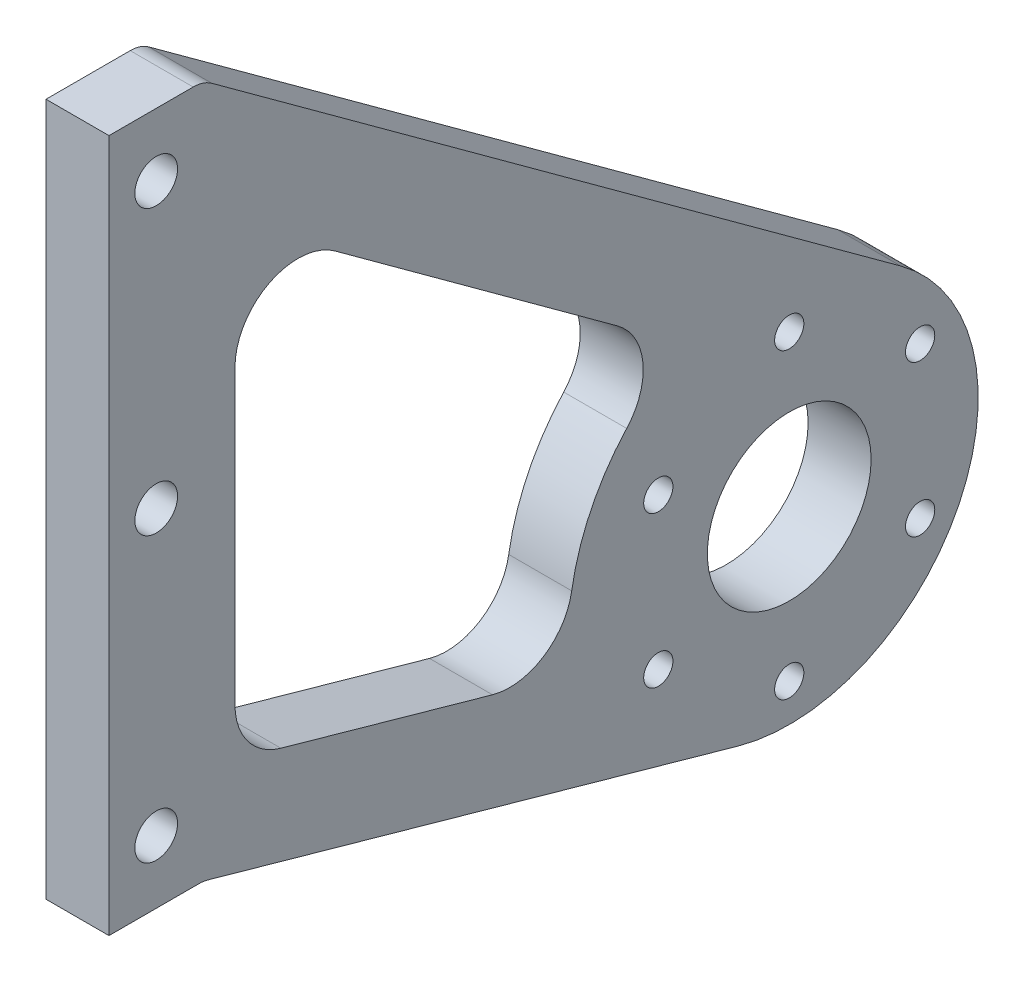
SolidWorks part; units mm, degrees
material "6061-T6 (SS)"
ref_plane "Front Plane" through (0, 0, 0) normal (0, 0, 1) x (1, 0, 0)
ref_plane "Top Plane" through (0, 0, 0) normal (0, 1, 0) x (1, 0, 0)
ref_plane "Right Plane" through (0, 0, 0) normal (1, 0, 0) x (0, 0, -1)
sketch "Sketch1" plane through (0, 0, 0) normal (1, 0, 0) x (0, 0, -1)
  line L0 (0, -34.925) -> (0, 34.925)
  line L1 (0, 34.925) -> (9.525, 34.925)
  line L2 (9.525, 34.925) -> (79.8091, -16.3614)
  line L4 (0, -34.925) -> (9.525, -34.925)
  line L5 (9.525, -34.925) -> (63.4208, -50.0881)
  arc A0 (79.8091, -16.3614) -> (63.4208, -50.0881) centre (68.58, -31.75) cw
  point P1 (0, 0)
  dimension "D5" = 19.05
  dimension "D1" = 69.85
  dimension "D2" = 9.525
  dimension "D3" = 68.58
  dimension "D4" = 31.75
extrude "Boss-Extrude1" add sketch "Sketch1" along normal mid plane 6.35
sketch "Sketch2" plane through (3.175, 0, 0) normal (1, 0, 0) x (0, 0, -1)
  circle A0 centre (68.58, -31.75) radius 8.255
  dimension "D1" = 16.51
extrude "Cut-Extrude1" cut sketch "Sketch2" against normal through all
hole_wizard "#8 Clearance Hole1" positions "Sketch4" profile "Sketch5" hole size "#8" standard "Ansi Inch" end condition through all
sketch "Sketch4" plane through (3.175, 0, 0) normal (1, 0, 0) x (0, 0, -1)
  line L0 (4.7625, 34.925) -> (4.7625, -34.925) construction
  line L2 (0, 34.925) -> (9.525, 34.925) construction
  line L4 (0, -34.925) -> (9.525, -34.925) construction
  point P0 (4.7625, 0)
  point P17 (4.7625, 28.575)
  point P19 (4.7625, -28.575)
  dimension "D1" = 28.575
  dimension "D2" = 28.575
sketch "Sketch5" plane through (3.175, 0, -4.7625) normal (0, 1, 0) x (0, 0, -1)
  line L0 (0, 0) -> (0, 6.35)
  line L1 (0, 6.35) -> (2.1526, 6.35)
  line L2 (2.1526, 6.35) -> (2.1526, 0)
  line L5 (2.1526, 0) -> (0, 0)
  line L11 (0, -6.35) -> (0, 107.95) construction
  dimension "Thru Hole Dia." = 4.3053
  dimension "Thru Hole Depth" = 6.35
hole_wizard "#4 Clearance Hole1" positions "Sketch7" profile "Sketch6" hole size "#4" standard "Ansi Inch"
sketch "Sketch7" plane through (3.175, 0, 0) normal (1, 0, 0) x (0, 0, -1)
  line L0 (68.58, -16.51) -> (68.58, -31.75) construction
  point P0 (68.58, -16.51)
  dimension "D1" = 15.24
sketch "Sketch6" plane through (3.175, -16.51, -68.58) normal (0, 1, 0) x (0, 0, -1)
  line L0 (0, 0) -> (0, 7.2352)
  line L1 (0, 7.2352) -> (1.4732, 6.35)
  line L2 (1.4732, 6.35) -> (1.4732, 0)
  line L5 (1.4732, 0) -> (0, 0)
  line L10 (0, 7.2352) -> (-1.4732, 6.35) construction
  line L11 (0, -6.35) -> (0, 107.95) construction
  dimension "Hole Dia." = 2.9464
  dimension "Hole Depth" = 6.35
  dimension "Drill Angle" = 118
pattern_circular "CirPattern1" count 6 over 360 about axis through (0, -31.75, -68.58) along (1, 0, 0) of "#4 Clearance Hole1"
fillet "Fillet1" radius 3.175 2 edges at (0, 34.925, -9.525) (0, -34.925, -9.525)
sketch "Sketch8" plane through (3.175, 0, 0) normal (1, 0, 0) x (0, 0, -1)
  line L0 (12.7, -25.9235) -> (12.7, 20.8169)
  line L1 (12.7, 20.8169) -> (57.9735, -12.2192)
  line L2 (79.8091, -16.3614) -> (10.3613, 34.3148) construction
  line L3 (46.6704, -35.4807) -> (12.7, -25.9235)
  line L4 (9.9468, -35.0437) -> (63.4208, -50.0881) construction
  line L6 (0, 34.925) -> (0, -34.925) construction
  arc A0 (57.9735, -12.2192) -> (46.6704, -35.4807) centre (68.58, -31.75) ccw
  dimension "D1" = 44.45
  dimension "D2" = 9.525
  dimension "D3" = 9.525
  dimension "D4" = 12.7
extrude "Cut-Extrude2" cut sketch "Sketch8" against normal through all
fillet "Fillet2" radius 6.35 4 edges at (0, -25.9235, -12.7) (0, 20.8169, -12.7) (0, -12.2192, -57.9735) (0, -35.4807, -46.6704)
